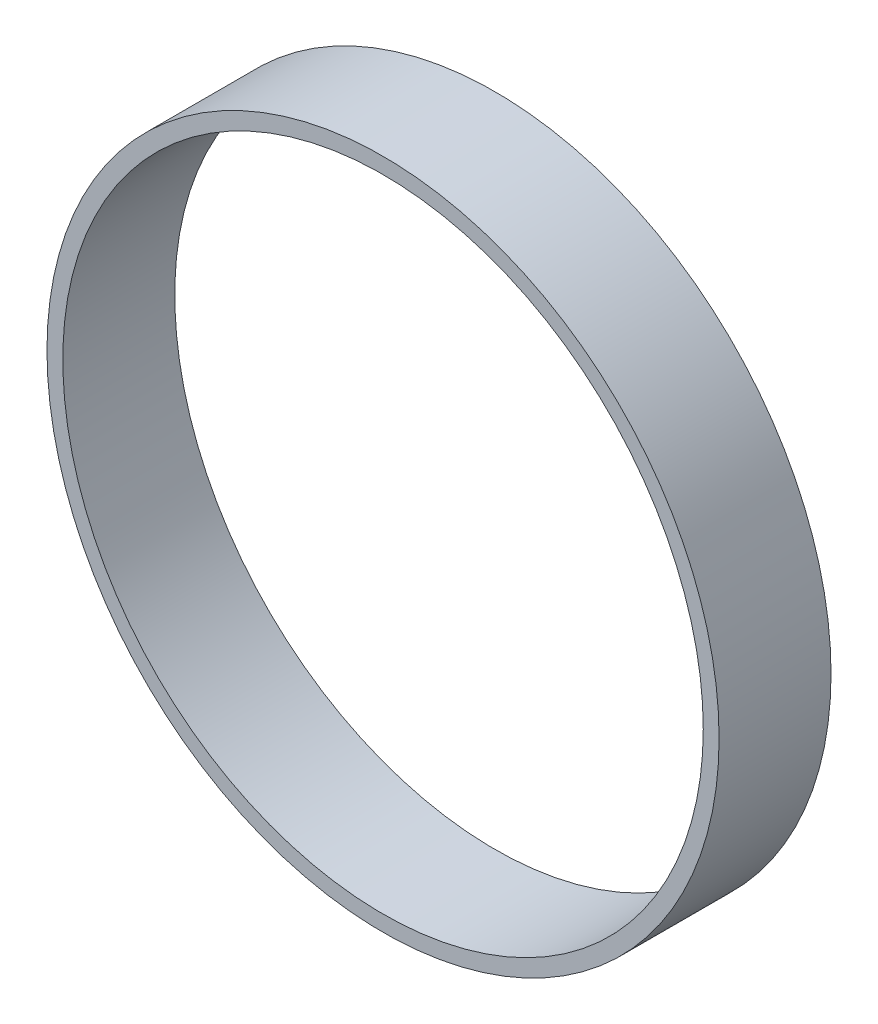
SolidWorks part; units mm, degrees
ref_plane "Front Plane" through (0, 0, 0) normal (0, 0, 1) x (1, 0, 0)
ref_plane "Top Plane" through (0, 0, 0) normal (0, 1, 0) x (1, 0, 0)
ref_plane "Right Plane" through (0, 0, 0) normal (1, 0, 0) x (0, 0, -1)
sketch "Sketch1" plane through (0, 0, 0) normal (0, 0, 1) x (1, 0, 0)
  circle A0 centre (0, 0) radius 14.8971
  circle A1 centre (0, 0) radius 15.6337
  dimension "D1" = 0.7366
  dimension "D2" = 29.7942
  dimension "D3" = 31.2674
extrude "Extrude1" add sketch "Sketch1" along normal blind 5.207
